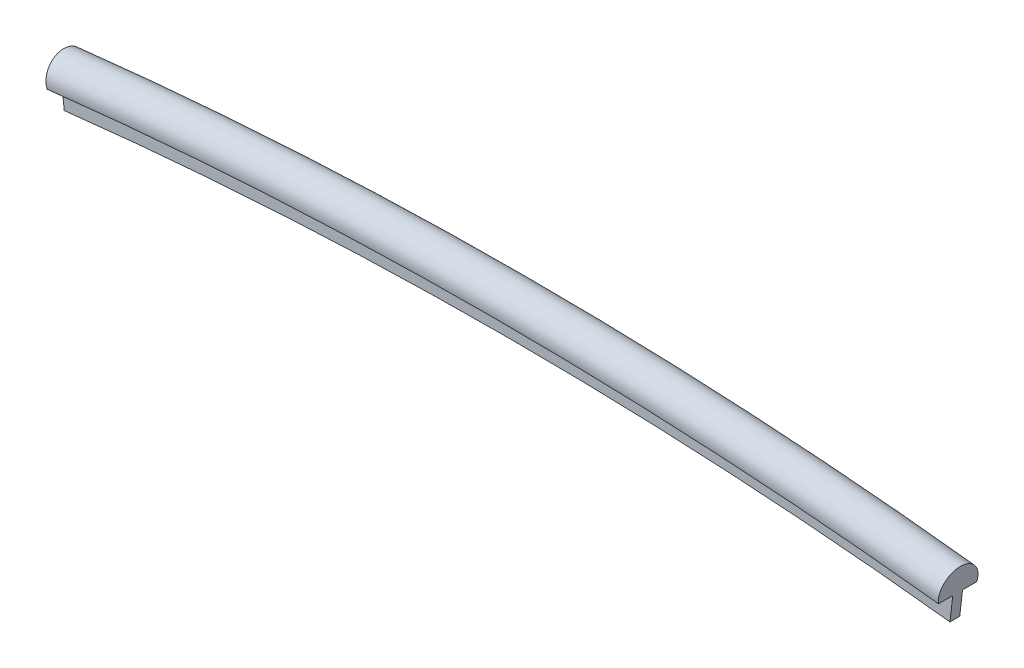
SolidWorks part; units mm, degrees
ref_plane "Front Plane" through (0, 0, 0) normal (0, 0, 1) x (1, 0, 0)
ref_plane "Top Plane" through (0, 0, 0) normal (0, 1, 0) x (1, 0, 0)
ref_plane "Right Plane" through (0, 0, 0) normal (1, 0, 0) x (0, 0, -1)
sketch "Sketch2" plane through (0, 0, 0) normal (1, 0, 0) x (0, 0, -1)
  line L0 (0, 241.3) -> (0, 0) construction
  line L2 (0, 241.3) -> (0, 239.8) construction
  line L3 (0, 239.8) -> (0.3, 239.8)
  line L4 (0, 239.8) -> (-0.3, 239.8)
  line L5 (-0.3, 239.8) -> (-0.3, 241.3)
  line L6 (0.3, 239.8) -> (0.3, 241.3)
  line L7 (0, 241.3) -> (0, 242.8) construction
  line L8 (-1.18, 241.3) -> (-0.3, 241.3)
  line L9 (0.3, 241.3) -> (1.18, 241.3)
  arc A0 (-1.18, 241.3) -> (1.18, 241.3) centre (0, 241.586) cw
  point P14 (0, 241.3)
ref_axis "Axis2" through (0, 0, 70.5976) along (0, 0, -1)
revolve "Revolve1" add sketch "Sketch2" angle 6.526 about axis through (0, 0, 70.5976) along (0, 0, -1)
